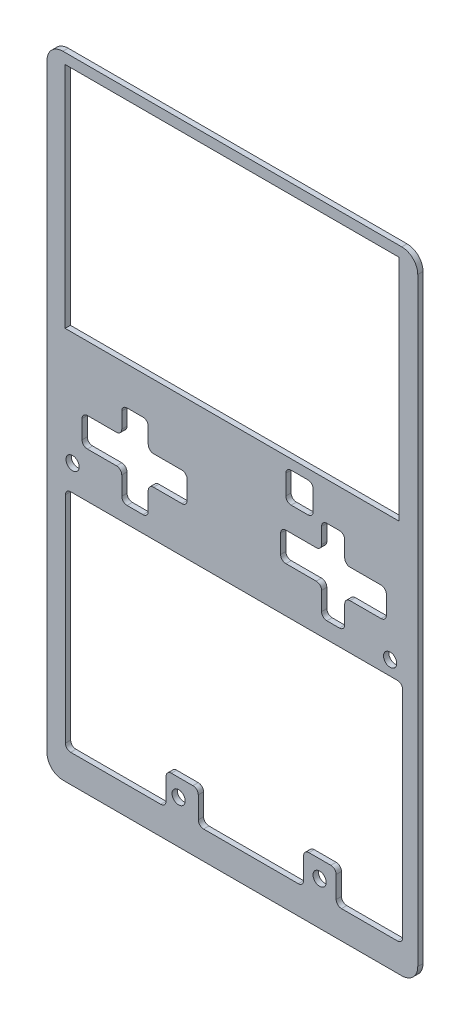
SolidWorks part; units mm, degrees
material "Plastique personnalisé"
ref_plane "Plan de face" through (0, 0, 0) normal (0, 0, 1) x (1, 0, 0)
ref_plane "Plan de dessus" through (0, 0, 0) normal (0, 1, 0) x (1, 0, 0)
ref_plane "Plan de droite" through (0, 0, 0) normal (1, 0, 0) x (0, 0, -1)
sketch "Esquisse1" plane through (0, 0, 0) normal (0, 0, 1) x (1, 0, 0)
  line L1 (-32.05, -59.71) -> (32.05, -59.71)
  line L2 (-35.07, -56.69) -> (-35.07, 56.69)
  line L3 (-32.05, 59.71) -> (32.05, 59.71)
  line L4 (35.07, -56.69) -> (35.07, 56.69)
  line L5 (-35.07, -59.71) -> (35.07, 59.71) construction
  line L6 (-35.07, 59.71) -> (35.07, -59.71) construction
  arc A0 (32.05, -59.71) -> (35.07, -56.69) centre (32.05, -56.69) ccw
  arc A1 (-32.05, -59.71) -> (-35.07, -56.69) centre (-32.05, -56.69) cw
  arc A2 (-35.07, 56.69) -> (-32.05, 59.71) centre (-32.05, 56.69) cw
  arc A3 (32.05, 59.71) -> (35.07, 56.69) centre (32.05, 56.69) cw
  point P0 (0, 0)
  dimension "D3" = 3.02
  dimension "D1" = 70.14
  dimension "D2" = 119.42
extrude "Boss.-Extru.1" add sketch "Esquisse1" along normal blind 1
sketch "Esquisse2" plane through (0, 0, 1) normal (0, 0, 1) x (1, 0, 0)
  line L1 (-31.6288, 57.7474) -> (31.4925, 57.7474)
  line L2 (-31.6288, 57.7474) -> (-31.6288, 14.5199)
  line L3 (-31.6288, 14.5199) -> (31.4925, 14.5199)
  line L4 (31.4925, 57.7474) -> (31.4925, 14.5199)
extrude "Enlèv. mat.-Extru.1" cut sketch "Esquisse2" against normal blind 1
sketch "Esquisse3" plane through (0, 0, 1) normal (0, 0, 1) x (1, 0, 0)
  line L0 (-5.4503, -54.4032) -> (12.4822, -54.4032)
  line L1 (-30.5816, -11.7237) -> (31.2267, -11.7237)
  line L2 (-31.5816, -12.7237) -> (-31.5816, -53.4032)
  line L3 (-30.5816, -54.4032) -> (-13.5366, -54.4032)
  line L4 (32.2267, -12.7237) -> (32.2267, -53.4032)
  line L6 (-12.5366, -53.4032) -> (-12.5366, -49.3111)
  line L7 (-11.5366, -48.3111) -> (-7.4503, -48.3111)
  line L8 (-6.4503, -53.4032) -> (-6.4503, -49.3111)
  line L10 (13.4822, -53.4032) -> (13.4822, -49.3111)
  line L11 (14.4822, -48.3111) -> (18.6393, -48.3111)
  line L12 (19.6393, -53.4032) -> (19.6393, -49.3111)
  line L13 (20.6393, -54.4032) -> (31.2267, -54.4032)
  line L14 (-14.9104, 2.3424) -> (-9.548, 2.3424)
  line L15 (-19.9227, 7.3361) -> (-16.9104, 7.3361)
  line L16 (-20.9227, 6.3361) -> (-20.9227, 3.3424)
  line L17 (-19.9227, -8.6332) -> (-16.9104, -8.6332)
  line L18 (-15.9104, 6.3361) -> (-15.9104, 3.3424)
  line L19 (-27.4346, 2.3424) -> (-21.9227, 2.3424)
  line L20 (-28.4346, 1.3424) -> (-28.4346, -2.1454)
  line L21 (-27.4346, -3.1454) -> (-21.9227, -3.1454)
  line L22 (-8.548, 1.3424) -> (-8.548, -2.1454)
  line L23 (-15.9104, -4.1454) -> (-15.9104, -7.6332)
  line L24 (-20.9227, -4.1454) -> (-20.9227, -7.6332)
  line L25 (-14.9104, -3.1454) -> (-9.548, -3.1454)
  line L26 (22.2563, 2.3424) -> (28.1316, 2.3424)
  line L27 (10.1249, 2.3424) -> (15.8698, 2.3424)
  line L28 (9.1249, 1.3424) -> (9.1249, -2.1454)
  line L29 (10.1249, -3.1454) -> (15.8698, -3.1454)
  line L30 (29.1316, 1.3424) -> (29.1316, -2.1454)
  line L31 (17.8698, 7.3361) -> (20.2563, 7.3361)
  line L32 (16.8698, 6.3361) -> (16.8698, 3.3424)
  line L33 (17.8698, -8.6332) -> (20.2563, -8.6332)
  line L34 (21.2563, 6.3361) -> (21.2563, 3.3424)
  line L35 (21.2563, -4.1454) -> (21.2563, -7.6332)
  line L36 (16.8698, -4.1454) -> (16.8698, -7.6332)
  line L37 (22.2563, -3.1454) -> (28.1316, -3.1454)
  line L39 (11.1141, 12.6558) -> (14.2942, 12.6558)
  line L40 (10.1141, 11.6558) -> (10.1141, 7.9303)
  line L41 (11.1141, 6.9303) -> (14.2942, 6.9303)
  line L42 (15.2942, 11.6558) -> (15.2942, 7.9303)
  arc A0 (-31.5816, -53.4032) -> (-30.5816, -54.4032) centre (-30.5816, -53.4032) ccw
  arc A1 (-13.5366, -54.4032) -> (-12.5366, -53.4032) centre (-13.5366, -53.4032) ccw
  arc A2 (-12.5366, -49.3111) -> (-11.5366, -48.3111) centre (-11.5366, -49.3111) cw
  arc A3 (-7.4503, -48.3111) -> (-6.4503, -49.3111) centre (-7.4503, -49.3111) cw
  arc A4 (-5.4503, -54.4032) -> (-6.4503, -53.4032) centre (-5.4503, -53.4032) cw
  arc A5 (12.4822, -54.4032) -> (13.4822, -53.4032) centre (12.4822, -53.4032) ccw
  arc A6 (13.4822, -49.3111) -> (14.4822, -48.3111) centre (14.4822, -49.3111) cw
  arc A7 (18.6393, -48.3111) -> (19.6393, -49.3111) centre (18.6393, -49.3111) cw
  arc A8 (20.6393, -54.4032) -> (19.6393, -53.4032) centre (20.6393, -53.4032) cw
  arc A9 (31.2267, -54.4032) -> (32.2267, -53.4032) centre (31.2267, -53.4032) ccw
  arc A10 (31.2267, -11.7237) -> (32.2267, -12.7237) centre (31.2267, -12.7237) cw
  arc A11 (-30.5816, -11.7237) -> (-31.5816, -12.7237) centre (-30.5816, -12.7237) ccw
  arc A12 (-27.4346, 2.3424) -> (-28.4346, 1.3424) centre (-27.4346, 1.3424) ccw
  arc A13 (-28.4346, -2.1454) -> (-27.4346, -3.1454) centre (-27.4346, -2.1454) ccw
  arc A14 (-20.9227, -4.1454) -> (-21.9227, -3.1454) centre (-21.9227, -4.1454) ccw
  arc A15 (-20.9227, -7.6332) -> (-19.9227, -8.6332) centre (-19.9227, -7.6332) ccw
  arc A16 (-16.9104, -8.6332) -> (-15.9104, -7.6332) centre (-16.9104, -7.6332) ccw
  arc A17 (-15.9104, -4.1454) -> (-14.9104, -3.1454) centre (-14.9104, -4.1454) cw
  arc A18 (-9.548, -3.1454) -> (-8.548, -2.1454) centre (-9.548, -2.1454) ccw
  arc A19 (-9.548, 2.3424) -> (-8.548, 1.3424) centre (-9.548, 1.3424) cw
  arc A20 (-14.9104, 2.3424) -> (-15.9104, 3.3424) centre (-14.9104, 3.3424) cw
  arc A21 (-21.9227, 2.3424) -> (-20.9227, 3.3424) centre (-21.9227, 3.3424) ccw
  arc A22 (-19.9227, 7.3361) -> (-20.9227, 6.3361) centre (-19.9227, 6.3361) ccw
  arc A23 (-16.9104, 7.3361) -> (-15.9104, 6.3361) centre (-16.9104, 6.3361) cw
  arc A24 (16.8698, -4.1454) -> (15.8698, -3.1454) centre (15.8698, -4.1454) ccw
  arc A25 (9.1249, -2.1454) -> (10.1249, -3.1454) centre (10.1249, -2.1454) ccw
  arc A26 (10.1249, 2.3424) -> (9.1249, 1.3424) centre (10.1249, 1.3424) ccw
  arc A27 (15.8698, 2.3424) -> (16.8698, 3.3424) centre (15.8698, 3.3424) ccw
  arc A28 (22.2563, 2.3424) -> (21.2563, 3.3424) centre (22.2563, 3.3424) cw
  arc A29 (16.8698, -7.6332) -> (17.8698, -8.6332) centre (17.8698, -7.6332) ccw
  arc A30 (20.2563, -8.6332) -> (21.2563, -7.6332) centre (20.2563, -7.6332) ccw
  arc A31 (21.2563, -4.1454) -> (22.2563, -3.1454) centre (22.2563, -4.1454) cw
  arc A32 (28.1316, -3.1454) -> (29.1316, -2.1454) centre (28.1316, -2.1454) ccw
  arc A33 (28.1316, 2.3424) -> (29.1316, 1.3424) centre (28.1316, 1.3424) cw
  arc A34 (20.2563, 7.3361) -> (21.2563, 6.3361) centre (20.2563, 6.3361) cw
  arc A35 (17.8698, 7.3361) -> (16.8698, 6.3361) centre (17.8698, 6.3361) ccw
  arc A36 (14.2942, 6.9303) -> (15.2942, 7.9303) centre (14.2942, 7.9303) ccw
  arc A37 (10.1141, 7.9303) -> (11.1141, 6.9303) centre (11.1141, 7.9303) ccw
  arc A38 (11.1141, 12.6558) -> (10.1141, 11.6558) centre (11.1141, 11.6558) ccw
  arc A39 (14.2942, 12.6558) -> (15.2942, 11.6558) centre (14.2942, 11.6558) cw
  point P52 (13.4822, -54.4032)
  point P77 (-15.9104, -3.1454)
  point P106 (21.2563, -3.1454)
  dimension "D1" = 1
extrude "Enlèv. mat.-Extru.2" cut sketch "Esquisse3" against normal blind 1
sketch "Esquisse4" plane through (0, 0, 1) normal (0, 0, 1) x (1, 0, 0)
  circle A0 centre (-30.226, -6.858) radius 1.25
  circle A1 centre (29.845, -9.017) radius 1.25
  circle A2 centre (16.51, -51.562) radius 1.25
  circle A3 centre (-10.16, -51.562) radius 1.25
extrude "Enlèv. mat.-Extru.3" cut sketch "Esquisse4" against normal blind 1
